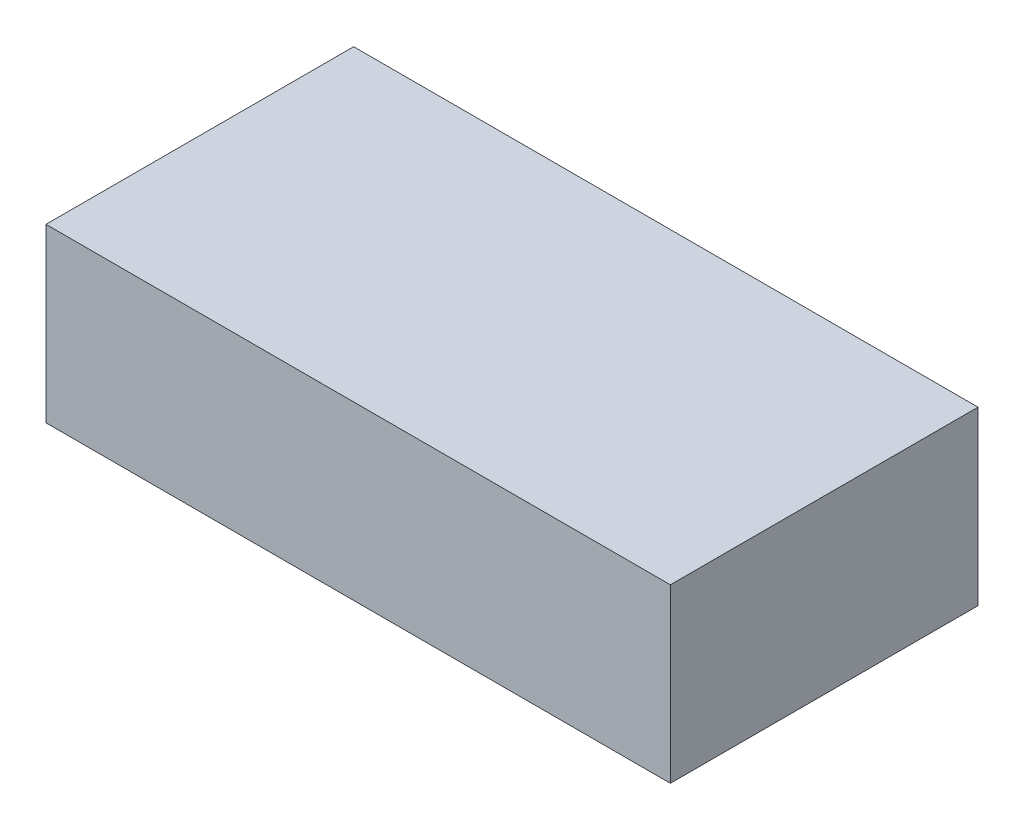
SolidWorks part; units mm, degrees
ref_plane "前视基准面" through (0, 0, 0) normal (0, 0, 1) x (1, 0, 0)
ref_plane "上视基准面" through (0, 0, 0) normal (0, 1, 0) x (1, 0, 0)
ref_plane "右视基准面" through (0, 0, 0) normal (1, 0, 0) x (0, 0, -1)
sketch "草图1" plane through (0, 0, 0) normal (0, 1, 0) x (1, 0, 0)
  line L1 (-34.5, 17) -> (34.5, 17)
  line L2 (-34.5, 17) -> (-34.5, -17)
  line L3 (-34.5, -17) -> (34.5, -17)
  line L4 (34.5, 17) -> (34.5, -17)
  line L5 (-34.5, 17) -> (34.5, -17) construction
  line L6 (-34.5, -17) -> (34.5, 17) construction
  point P0 (0, 0)
  dimension "D1" = 69
  dimension "D2" = 34
extrude "凸台-拉伸1" add sketch "草图1" along normal blind 19
